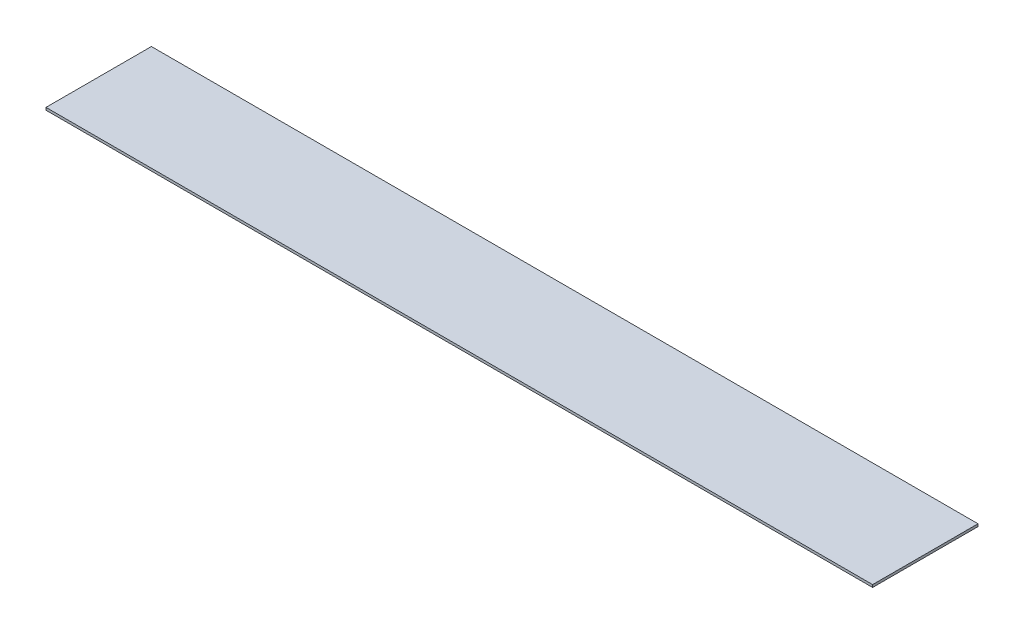
SolidWorks part; units mm, degrees
material "Polyethylene Cross-Linked"
ref_plane "Front Plane" through (0, 0, 0) normal (0, 0, 1) x (1, 0, 0)
ref_plane "Top Plane" through (0, 0, 0) normal (0, 1, 0) x (1, 0, 0)
ref_plane "Right Plane" through (0, 0, 0) normal (1, 0, 0) x (0, 0, -1)
sketch "Sketch1" plane through (0, 0, 0) normal (0, 1, 0) x (1, 0, 0)
  line L1 (-82.55, 10.525) -> (82.55, 10.525)
  line L2 (-82.55, 10.525) -> (-82.55, -10.525)
  line L3 (-82.55, -10.525) -> (82.55, -10.525)
  line L4 (82.55, 10.525) -> (82.55, -10.525)
  line L5 (-82.55, 10.525) -> (82.55, -10.525) construction
  line L6 (-82.55, -10.525) -> (82.55, 10.525) construction
  point P0 (0, 0)
  dimension "D1" = 21.05
  dimension "D2" = 165.1
extrude "Boss-Extrude1" add sketch "Sketch1" along normal mid plane 0.5
equation "\"D2@Sketch1\"=6.5in"
equation "\"D1@Sketch1\"=2in/2-4.35mm"
